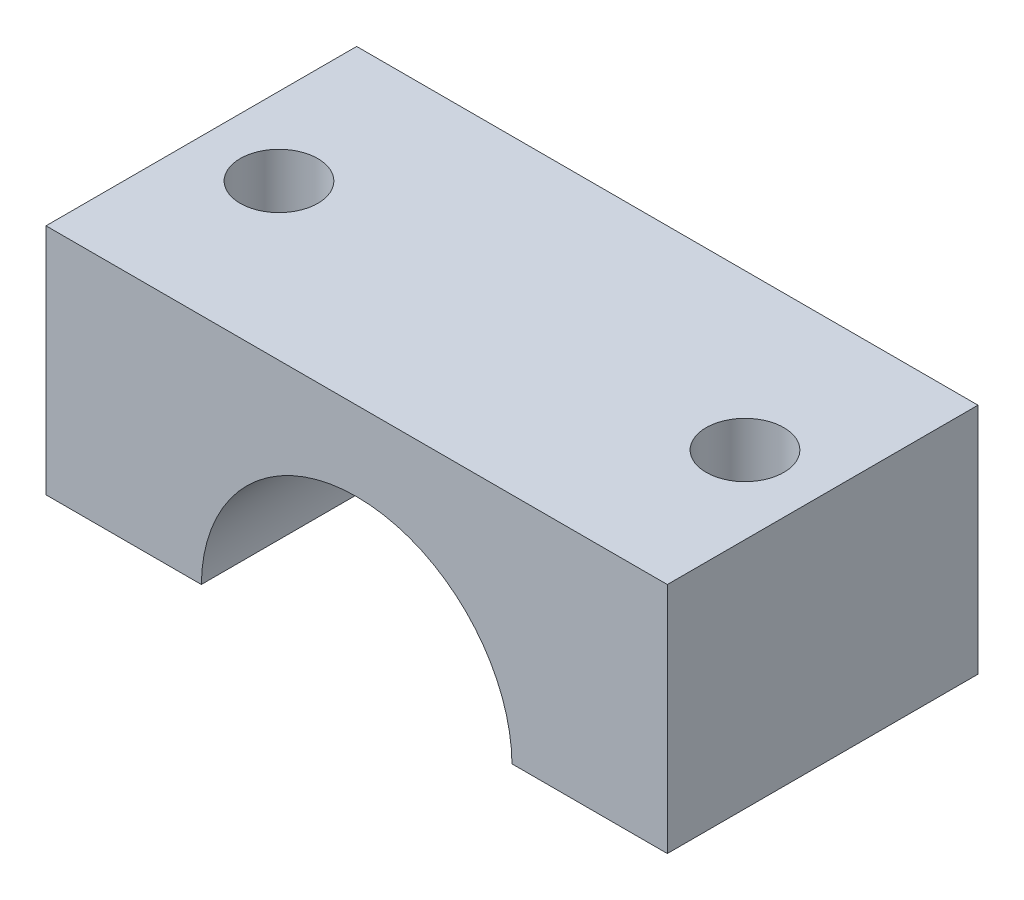
SolidWorks part; units mm, degrees
material "6061-T6 (SS)"
ref_plane "Front Plane" through (0, 0, 0) normal (0, 0, 1) x (1, 0, 0)
ref_plane "Top Plane" through (0, 0, 0) normal (0, 1, 0) x (1, 0, 0)
ref_plane "Right Plane" through (0, 0, 0) normal (1, 0, 0) x (0, 0, -1)
sketch "Sketch1" plane through (0, 0, 0) normal (0, 1, 0) x (1, 0, 0)
  line L1 (-25.4, -12.7) -> (25.4, -12.7)
  line L2 (-25.4, -12.7) -> (-25.4, 12.7)
  line L3 (-25.4, 12.7) -> (25.4, 12.7)
  line L4 (25.4, -12.7) -> (25.4, 12.7)
  line L5 (-25.4, -12.7) -> (25.4, 12.7) construction
  line L6 (-25.4, 12.7) -> (25.4, -12.7) construction
  point P0 (0, 0)
  dimension "D1" = 50.8
  dimension "D2" = 25.4
extrude "Block" add sketch "Sketch1" along normal blind 19.05
sketch "Sketch2" plane through (0, 0, 12.7) normal (0, 0, 1) x (1, 0, 0)
  line L0 (-25.4, 0) -> (25.4, 0) construction
  circle A0 centre (0, -0.127) radius 12.7
  dimension "D2" = 25.4
  dimension "D1" = 0.127
extrude "ShaftHole" cut sketch "Sketch2" against normal through all
sketch "Bolt Hole Pattern" plane through (0, 19.05, 0) normal (0, 1, 0) x (1, 0, 0)
  line L0 (-25.4, 0) -> (25.4, 0) construction
  line L1 (-25.4, 12.7) -> (-25.4, -12.7) construction
  line L2 (25.4, -12.7) -> (25.4, 12.7) construction
  line L3 (0, 12.7) -> (0, -12.7) construction
  line L4 (25.4, 12.7) -> (-25.4, 12.7) construction
  line L5 (-25.4, -12.7) -> (25.4, -12.7) construction
  point P7 (19.05, 0)
  point P15 (-19.05, 0)
  dimension "D1" = 19.05
hole_wizard "Clamping Holes" positions "Sketch5" profile "Sketch4" hole size "1/4" standard "ANSI Inch" end condition through all
sketch "Sketch5" plane through (0, 19.05, 0) normal (0, 1, 0) x (1, 0, 0)
  point P0 (-19.05, 0)
  point P3 (19.05, 0)
sketch "Sketch4" plane through (-19.05, 19.05, 0) normal (1, 0, 0) x (0, 0, 1)
  line L0 (0, 0) -> (0, 19.05)
  line L1 (0, 19.05) -> (3.175, 19.05)
  line L2 (3.175, 19.05) -> (3.175, 0)
  line L5 (3.175, 0) -> (0, 0)
  line L11 (0, -6.35) -> (0, 107.95) construction
  dimension "Thru Hole Dia." = 6.35
  dimension "Thru Hole Depth" = 19.05
